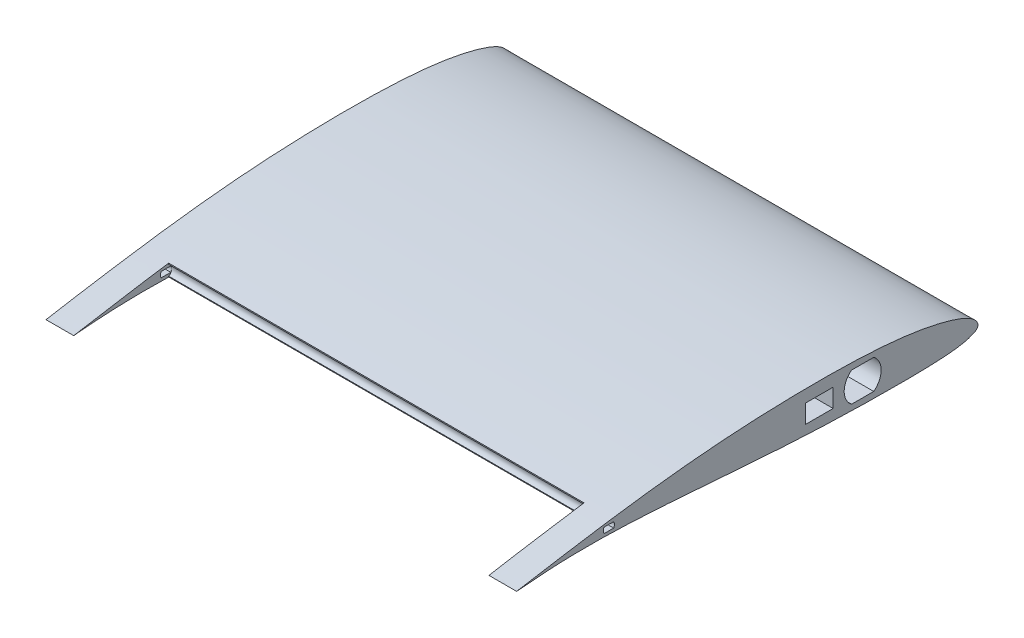
SolidWorks part; units mm, degrees
material "Foam"
ref_plane "Piano frontale" through (0, 0, 0) normal (0, 0, 1) x (1, 0, 0)
ref_plane "Piano superiore" through (0, 0, 0) normal (0, 1, 0) x (1, 0, 0)
ref_plane "Piano destro" through (0, 0, 0) normal (1, 0, 0) x (0, 0, -1)
curve "Curva1"
  spline degree 3 poles (0, 0.1724, 248.285) (0, -0.053, 250.4273) (0, 0.2462, 248.3284) (0, 0.5529, 246.6445) (0, 1.2459, 242.6221) (0, 2.0989, 237.7464) (0, 3.1818, 231.3634) (0, 4.2933, 223.9772) (0, 5.7312, 215.5604) (0, 7.1315, 206.3004) (0, 8.6324, 196.1631) (0, 10.1162, 185.3524) (0, 11.5493, 173.9891) (0, 12.8816, 162.1914) (0, 14.0593, 150.0724) (0, 15.0523, 137.7438) (0, 15.8256, 125.3116) (0, 16.3834, 112.8888) (0, 16.7267, 100.597) (0, 16.8648, 88.5669) (0, 16.792, 76.9314) (0, 16.4941, 65.8165) (0, 15.9609, 55.3329) (0, 15.1594, 45.573) (0, 14.0978, 36.6074) (0, 12.7884, 28.4972) (0, 11.2839, 21.2988) (0, 9.6413, 15.0749) (0, 7.9136, 9.8809) (0, 6.1182, 5.7699) (0, 4.2384, 2.7289) (0, 2.3057, 0.8126) (0, 0.7927, 0.0312) (0, -0.4105, -0.0213) (0, -1.7115, 0.4949) (0, -2.8658, 2.6253) (0, -4.0404, 5.6977) (0, -4.9287, 10.0719) (0, -5.5974, 15.6262) (0, -6.0122, 22.4122) (0, -6.265, 30.3619) (0, -6.3814, 39.3972) (0, -6.3554, 49.3987) (0, -6.2185, 60.2453) (0, -5.9476, 71.8018) (0, -5.5368, 83.9408) (0, -4.9386, 96.5461) (0, -4.1527, 109.5201) (0, -3.2196, 122.7671) (0, -2.1909, 136.1764) (0, -1.148, 149.6158) (0, -0.1602, 162.9314) (0, 0.706, 175.9537) (0, 1.3896, 188.4999) (0, 1.8332, 200.3712) (0, 1.9676, 211.3376) (0, 1.8232, 221.1842) (0, 1.4973, 229.6804) (0, 1.0741, 236.8065) (0, 0.6857, 242.1894) (0, 0.3087, 246.5181) (0, 0.1724, 248.285) (0, -0.053, 250.4273) (0, 0.2462, 248.3284) knots -0.014202 -0.006329 -0.001589 0 0.001576 0.006211 0.01368 0.023764 0.036307 0.051658 0.068045 0.086769 0.107053 0.128647 0.151303 0.174786 0.19886 0.223309 0.247929 0.272522 0.296848 0.320648 0.343669 0.365658 0.3864 0.405741 0.423561 0.439779 0.454311 0.467034 0.477831 0.486643 0.493542 0.498786 0.50271 0.50309 0.505896 0.510322 0.516831 0.525521 0.536535 0.549945 0.565696 0.583577 0.603379 0.624844 0.647727 0.671743 0.696673 0.722357 0.748609 0.77521 0.801891 0.828329 0.854175 0.879074 0.902636 0.924421 0.943939 0.960827 0.974827 0.985798 0.993671 0.998411 1 1.001576 1.006211 1.01368 periodic
sketch "Schizzo1" plane through (0, 0, 0) normal (1, 0, 0) x (0, 0, -1)
  line L0 (-250, 0) -> (0.0001, 0.0174) construction
  line L1 (0.0001, 0.0174) -> (-0.0034, 50.0174) construction
  line L2 (-62.4999, 16.3096) -> (-62.4999, -6.155) construction
  line L3 (-200, 8.0593) -> (-200, 1.7757) construction
  line L4 (-93.4999, 10.0773) -> (-78.4999, 10.0773)
  line L5 (-93.4999, 10.0773) -> (-93.4999, 0.0773)
  line L6 (-93.4999, 0.0773) -> (-78.4999, 0.0773)
  line L7 (-78.4999, 10.0773) -> (-78.4999, 0.0773)
  circle A0 centre (-62.4999, 5.0773) radius 8
  arc A1 (-200, 8.0593) -> (-200, 1.7757) centre (-200, 4.9175) cw
  spline S0 degree 3 poles (-248.3284, 0.2462) (-250.4273, -0.053) (-248.285, 0.1724) (-246.5181, 0.3087) (-242.1894, 0.6857) (-236.8065, 1.0741) (-229.6804, 1.4973) (-221.1842, 1.8232) (-211.3376, 1.9676) (-200.3712, 1.8332) (-188.4999, 1.3896) (-175.9537, 0.706) (-162.9314, -0.1602) (-149.6158, -1.148) (-136.1764, -2.1909) (-122.7671, -3.2196) (-109.5201, -4.1527) (-96.5461, -4.9386) (-83.9408, -5.5368) (-71.8018, -5.9476) (-60.2453, -6.2185) (-49.3987, -6.3554) (-39.3972, -6.3814) (-30.3619, -6.265) (-22.4122, -6.0122) (-15.6262, -5.5974) (-10.0719, -4.9287) (-5.6977, -4.0404) (-2.6253, -2.8658) (-0.4949, -1.7115) (0.0213, -0.4105) (-0.0312, 0.7927) (-0.8126, 2.3057) (-2.7289, 4.2384) (-5.7699, 6.1182) (-9.8809, 7.9136) (-15.0749, 9.6413) (-21.2988, 11.2839) (-28.4972, 12.7884) (-36.6074, 14.0978) (-45.573, 15.1594) (-55.3329, 15.9609) (-65.8165, 16.4941) (-76.9314, 16.792) (-88.5669, 16.8648) (-100.597, 16.7267) (-112.8888, 16.3834) (-125.3116, 15.8256) (-137.7438, 15.0523) (-150.0724, 14.0593) (-162.1914, 12.8816) (-173.9891, 11.5493) (-185.3524, 10.1162) (-196.1631, 8.6324) (-206.3004, 7.1315) (-215.5604, 5.7312) (-223.9772, 4.2933) (-231.3634, 3.1818) (-237.7464, 2.0989) (-242.6221, 1.2459) (-246.6445, 0.5529) (-248.3284, 0.2462) (-250.4273, -0.053) (-248.285, 0.1724) knots -0.01368 -0.006211 -0.001576 0 0.001589 0.006329 0.014202 0.025173 0.039173 0.056061 0.075579 0.097364 0.120926 0.145825 0.171671 0.198109 0.22479 0.251391 0.277643 0.303327 0.328257 0.352273 0.375156 0.396621 0.416423 0.434304 0.450055 0.463465 0.474479 0.483169 0.489678 0.494104 0.49691 0.49729 0.501214 0.506458 0.513357 0.522169 0.532966 0.545689 0.560221 0.576439 0.594259 0.6136 0.634342 0.656331 0.679352 0.703152 0.727478 0.752071 0.776691 0.80114 0.825214 0.848697 0.871353 0.892947 0.913231 0.931955 0.948342 0.963693 0.976236 0.98632 0.993789 0.998424 1 1.001589 1.006329 1.014202 only from (-250, 0) to (-250, 0) construction
  spline S1 degree 3 poles (-200, 1.7757) (-196.2415, 1.6788) (-188.276, 1.3774) (-175.9537, 0.706) (-162.9314, -0.1602) (-149.6158, -1.148) (-136.1764, -2.1909) (-122.7671, -3.2196) (-109.5201, -4.1527) (-96.5461, -4.9386) (-83.9408, -5.5368) (-71.8018, -5.9476) (-60.2453, -6.2185) (-49.3987, -6.3554) (-39.3972, -6.3814) (-30.3619, -6.265) (-22.4122, -6.0122) (-15.6262, -5.5974) (-10.0719, -4.9287) (-5.6977, -4.0404) (-2.6253, -2.8658) (-0.4949, -1.7115) (0.0213, -0.4105) (-0.0312, 0.7927) (-0.8126, 2.3057) (-2.7289, 4.2384) (-5.7699, 6.1182) (-9.8809, 7.9136) (-15.0749, 9.6413) (-21.2988, 11.2839) (-28.4972, 12.7884) (-36.6074, 14.0978) (-45.573, 15.1594) (-55.3329, 15.9609) (-65.8165, 16.4941) (-76.9314, 16.792) (-88.5669, 16.8648) (-100.597, 16.7267) (-112.8888, 16.3834) (-125.3116, 15.8256) (-137.7438, 15.0523) (-150.0724, 14.0593) (-162.1914, 12.8816) (-173.9891, 11.5493) (-185.3524, 10.1162) (-193.973, 8.933) (-198.7936, 8.2355) (-200, 8.0593) knots 0.09869 0.09869 0.09869 0.09869 0.120926 0.145825 0.171671 0.198109 0.22479 0.251391 0.277643 0.303327 0.328257 0.352273 0.375156 0.396621 0.416423 0.434304 0.450055 0.463465 0.474479 0.483169 0.489678 0.494104 0.49691 0.49729 0.501214 0.506458 0.513357 0.522169 0.532966 0.545689 0.560221 0.576439 0.594259 0.6136 0.634342 0.656331 0.679352 0.703152 0.727478 0.752071 0.776691 0.80114 0.825214 0.848697 0.871353 0.892947 0.900158 0.900158 0.900158 0.900158
  point P12 (-78.4999, 5.0773)
  dimension "D3" = 16
  dimension "D1" = 50
  dimension "D2" = 62.5
  dimension "D4" = 15
  dimension "D5" = 10
  dimension "D6" = 16
  dimension "D7" = 50
  dimension "D8" = 6.2836
extrude "CorpoFoam" add sketch "Schizzo1" along normal blind 225
sketch "Schizzo2" plane through (225, 0, 0) normal (1, 0, 0) x (0, 0, -1)
  line L0 (-200, 8.0593) -> (-200, 1.7757) construction
  line L1 (-203.5, 8.2775) -> (-198.5, 8.2775)
  line L2 (-203.5, 8.2775) -> (-203.5, 1.7346)
  line L3 (-203.5, 1.7346) -> (-198.5, 1.7346)
  line L4 (-198.5, 8.2775) -> (-198.5, 1.7346)
  arc A0 (-200, 1.7757) -> (-200, 8.0593) centre (-200, 4.9175) ccw construction
  spline S0 degree 3 poles (-248.3284, 0.2462) (-250.4273, -0.053) (-248.285, 0.1724) (-246.5181, 0.3087) (-242.1894, 0.6857) (-236.8065, 1.0741) (-229.6804, 1.4973) (-221.1842, 1.8232) (-211.3376, 1.9676) (-200.3712, 1.8332) (-188.4999, 1.3896) (-175.9537, 0.706) (-162.9314, -0.1602) (-149.6158, -1.148) (-136.1764, -2.1909) (-122.7671, -3.2196) (-109.5201, -4.1527) (-96.5461, -4.9386) (-83.9408, -5.5368) (-71.8018, -5.9476) (-60.2453, -6.2185) (-49.3987, -6.3554) (-39.3972, -6.3814) (-30.3619, -6.265) (-22.4122, -6.0122) (-15.6262, -5.5974) (-10.0719, -4.9287) (-5.6977, -4.0404) (-2.6253, -2.8658) (-0.4949, -1.7115) (0.0213, -0.4105) (-0.0312, 0.7927) (-0.8126, 2.3057) (-2.7289, 4.2384) (-5.7699, 6.1182) (-9.8809, 7.9136) (-15.0749, 9.6413) (-21.2988, 11.2839) (-28.4972, 12.7884) (-36.6074, 14.0978) (-45.573, 15.1594) (-55.3329, 15.9609) (-65.8165, 16.4941) (-76.9314, 16.792) (-88.5669, 16.8648) (-100.597, 16.7267) (-112.8888, 16.3834) (-125.3116, 15.8256) (-137.7438, 15.0523) (-150.0724, 14.0593) (-162.1914, 12.8816) (-173.9891, 11.5493) (-185.3524, 10.1162) (-196.1631, 8.6324) (-206.3004, 7.1315) (-215.5604, 5.7312) (-223.9772, 4.2933) (-231.3634, 3.1818) (-237.7464, 2.0989) (-242.6221, 1.2459) (-246.6445, 0.5529) (-248.3284, 0.2462) (-250.4273, -0.053) (-248.285, 0.1724) knots -0.01368 -0.006211 -0.001576 0 0.001589 0.006329 0.014202 0.025173 0.039173 0.056061 0.075579 0.097364 0.120926 0.145825 0.171671 0.198109 0.22479 0.251391 0.277643 0.303327 0.328257 0.352273 0.375156 0.396621 0.416423 0.434304 0.450055 0.463465 0.474479 0.483169 0.489678 0.494104 0.49691 0.49729 0.501214 0.506458 0.513357 0.522169 0.532966 0.545689 0.560221 0.576439 0.594259 0.6136 0.634342 0.656331 0.679352 0.703152 0.727478 0.752071 0.776691 0.80114 0.825214 0.848697 0.871353 0.892947 0.913231 0.931955 0.948342 0.963693 0.976236 0.98632 0.993789 0.998424 1 1.001589 1.006329 1.014202 only from (-250, 0) to (-250, 0) construction
  dimension "D1" = 5
  dimension "D2" = 1.5
extrude "SmussoPosteriore" cut sketch "Schizzo2" against normal through all
sketch "Schizzo3" plane through (225, 0, 0) normal (1, 0, 0) x (0, 0, -1)
  line L1 (-93.4999, 10.0773) -> (-78.4999, 10.0773)
  line L2 (-93.4999, 10.0773) -> (-93.4999, 0.0773)
  line L3 (-93.4999, 0.0773) -> (-78.4999, 0.0773)
  line L4 (-78.4999, 10.0773) -> (-78.4999, 0.0773)
  circle A0 centre (-62.4999, 5.0773) radius 8
  circle A1 centre (-62.4999, 5.0773) radius 8 construction
  spline S0 degree 3 poles (-248.3284, 0.2462) (-250.4273, -0.053) (-248.285, 0.1724) (-246.5181, 0.3087) (-242.1894, 0.6857) (-236.8065, 1.0741) (-229.6804, 1.4973) (-221.1842, 1.8232) (-211.3376, 1.9676) (-200.3712, 1.8332) (-188.4999, 1.3896) (-175.9537, 0.706) (-162.9314, -0.1602) (-149.6158, -1.148) (-136.1764, -2.1909) (-122.7671, -3.2196) (-109.5201, -4.1527) (-96.5461, -4.9386) (-83.9408, -5.5368) (-71.8018, -5.9476) (-60.2453, -6.2185) (-49.3987, -6.3554) (-39.3972, -6.3814) (-30.3619, -6.265) (-22.4122, -6.0122) (-15.6262, -5.5974) (-10.0719, -4.9287) (-5.6977, -4.0404) (-2.6253, -2.8658) (-0.4949, -1.7115) (0.0213, -0.4105) (-0.0312, 0.7927) (-0.8126, 2.3057) (-2.7289, 4.2384) (-5.7699, 6.1182) (-9.8809, 7.9136) (-15.0749, 9.6413) (-21.2988, 11.2839) (-28.4972, 12.7884) (-36.6074, 14.0978) (-45.573, 15.1594) (-55.3329, 15.9609) (-65.8165, 16.4941) (-76.9314, 16.792) (-88.5669, 16.8648) (-100.597, 16.7267) (-112.8888, 16.3834) (-125.3116, 15.8256) (-137.7438, 15.0523) (-150.0724, 14.0593) (-162.1914, 12.8816) (-173.9891, 11.5493) (-185.3524, 10.1162) (-196.1631, 8.6324) (-206.3004, 7.1315) (-215.5604, 5.7312) (-223.9772, 4.2933) (-231.3634, 3.1818) (-237.7464, 2.0989) (-242.6221, 1.2459) (-246.6445, 0.5529) (-248.3284, 0.2462) (-250.4273, -0.053) (-248.285, 0.1724) knots -0.01368 -0.006211 -0.001576 0 0.001589 0.006329 0.014202 0.025173 0.039173 0.056061 0.075579 0.097364 0.120926 0.145825 0.171671 0.198109 0.22479 0.251391 0.277643 0.303327 0.328257 0.352273 0.375156 0.396621 0.416423 0.434304 0.450055 0.463465 0.474479 0.483169 0.489678 0.494104 0.49691 0.49729 0.501214 0.506458 0.513357 0.522169 0.532966 0.545689 0.560221 0.576439 0.594259 0.6136 0.634342 0.656331 0.679352 0.703152 0.727478 0.752071 0.776691 0.80114 0.825214 0.848697 0.871353 0.892947 0.913231 0.931955 0.948342 0.963693 0.976236 0.98632 0.993789 0.998424 1 1.001589 1.006329 1.014202 only from (-250, 0) to (-250, 0) construction
  spline S1 degree 3 poles (-248.3284, 0.2462) (-250.4273, -0.053) (-248.285, 0.1724) (-246.5181, 0.3087) (-242.1894, 0.6857) (-236.8065, 1.0741) (-229.6804, 1.4973) (-221.1842, 1.8232) (-211.3376, 1.9676) (-200.3712, 1.8332) (-188.4999, 1.3896) (-175.9537, 0.706) (-162.9314, -0.1602) (-149.6158, -1.148) (-136.1764, -2.1909) (-122.7671, -3.2196) (-109.5201, -4.1527) (-96.5461, -4.9386) (-83.9408, -5.5368) (-71.8018, -5.9476) (-60.2453, -6.2185) (-49.3987, -6.3554) (-39.3972, -6.3814) (-30.3619, -6.265) (-22.4122, -6.0122) (-15.6262, -5.5974) (-10.0719, -4.9287) (-5.6977, -4.0404) (-2.6253, -2.8658) (-0.4949, -1.7115) (0.0213, -0.4105) (-0.0312, 0.7927) (-0.8126, 2.3057) (-2.7289, 4.2384) (-5.7699, 6.1182) (-9.8809, 7.9136) (-15.0749, 9.6413) (-21.2988, 11.2839) (-28.4972, 12.7884) (-36.6074, 14.0978) (-45.573, 15.1594) (-55.3329, 15.9609) (-65.8165, 16.4941) (-76.9314, 16.792) (-88.5669, 16.8648) (-100.597, 16.7267) (-112.8888, 16.3834) (-125.3116, 15.8256) (-137.7438, 15.0523) (-150.0724, 14.0593) (-162.1914, 12.8816) (-173.9891, 11.5493) (-185.3524, 10.1162) (-196.1631, 8.6324) (-206.3004, 7.1315) (-215.5604, 5.7312) (-223.9772, 4.2933) (-231.3634, 3.1818) (-237.7464, 2.0989) (-242.6221, 1.2459) (-246.6445, 0.5529) (-248.3284, 0.2462) (-250.4273, -0.053) (-248.285, 0.1724) knots -0.01368 -0.006211 -0.001576 0 0.001589 0.006329 0.014202 0.025173 0.039173 0.056061 0.075579 0.097364 0.120926 0.145825 0.171671 0.198109 0.22479 0.251391 0.277643 0.303327 0.328257 0.352273 0.375156 0.396621 0.416423 0.434304 0.450055 0.463465 0.474479 0.483169 0.489678 0.494104 0.49691 0.49729 0.501214 0.506458 0.513357 0.522169 0.532966 0.545689 0.560221 0.576439 0.594259 0.6136 0.634342 0.656331 0.679352 0.703152 0.727478 0.752071 0.776691 0.80114 0.825214 0.848697 0.871353 0.892947 0.913231 0.931955 0.948342 0.963693 0.976236 0.98632 0.993789 0.998424 1 1.001589 1.006329 1.014202 only from (-250, 0) to (-250, 0)
extrude "LatoDestro" add sketch "Schizzo3" along normal blind 15
sketch "Schizzo4" plane through (0, 0, 0) normal (-1, 0, 0) x (0, 0, 1)
  line L1 (78.4999, 10.0773) -> (93.4999, 10.0773)
  line L2 (78.4999, 10.0773) -> (78.4999, 0.0773)
  line L3 (78.4999, 0.0773) -> (93.4999, 0.0773)
  line L4 (93.4999, 10.0773) -> (93.4999, 0.0773)
  circle A0 centre (62.4999, 5.0773) radius 8
  circle A1 centre (62.4999, 5.0773) radius 8 construction
  spline S0 degree 3 poles (248.285, 0.1724) (250.4273, -0.053) (248.3284, 0.2462) (246.6445, 0.5529) (242.6221, 1.2459) (237.7464, 2.0989) (231.3634, 3.1818) (223.9772, 4.2933) (215.5604, 5.7312) (206.3004, 7.1315) (196.1631, 8.6324) (185.3524, 10.1162) (173.9891, 11.5493) (162.1914, 12.8816) (150.0724, 14.0593) (137.7438, 15.0523) (125.3116, 15.8256) (112.8888, 16.3834) (100.597, 16.7267) (88.5669, 16.8648) (76.9314, 16.792) (65.8165, 16.4941) (55.3329, 15.9609) (45.573, 15.1594) (36.6074, 14.0978) (28.4972, 12.7884) (21.2988, 11.2839) (15.0749, 9.6413) (9.8809, 7.9136) (5.7699, 6.1182) (2.7289, 4.2384) (0.8126, 2.3057) (0.0312, 0.7927) (-0.0213, -0.4105) (0.4949, -1.7115) (2.6253, -2.8658) (5.6977, -4.0404) (10.0719, -4.9287) (15.6262, -5.5974) (22.4122, -6.0122) (30.3619, -6.265) (39.3972, -6.3814) (49.3987, -6.3554) (60.2453, -6.2185) (71.8018, -5.9476) (83.9408, -5.5368) (96.5461, -4.9386) (109.5201, -4.1527) (122.7671, -3.2196) (136.1764, -2.1909) (149.6158, -1.148) (162.9314, -0.1602) (175.9537, 0.706) (188.4999, 1.3896) (200.3712, 1.8332) (211.3376, 1.9676) (221.1842, 1.8232) (229.6804, 1.4973) (236.8065, 1.0741) (242.1894, 0.6857) (246.5181, 0.3087) (248.285, 0.1724) (250.4273, -0.053) (248.3284, 0.2462) knots -0.014202 -0.006329 -0.001589 0 0.001576 0.006211 0.01368 0.023764 0.036307 0.051658 0.068045 0.086769 0.107053 0.128647 0.151303 0.174786 0.19886 0.223309 0.247929 0.272522 0.296848 0.320648 0.343669 0.365658 0.3864 0.405741 0.423561 0.439779 0.454311 0.467034 0.477831 0.486643 0.493542 0.498786 0.50271 0.50309 0.505896 0.510322 0.516831 0.525521 0.536535 0.549945 0.565696 0.583577 0.603379 0.624844 0.647727 0.671743 0.696673 0.722357 0.748609 0.77521 0.801891 0.828329 0.854175 0.879074 0.902636 0.924421 0.943939 0.960827 0.974827 0.985798 0.993671 0.998411 1 1.001576 1.006211 1.01368 only from (250, 0) to (250, 0) construction
  spline S1 degree 3 poles (248.285, 0.1724) (250.4273, -0.053) (248.3284, 0.2462) (246.6445, 0.5529) (242.6221, 1.2459) (237.7464, 2.0989) (231.3634, 3.1818) (223.9772, 4.2933) (215.5604, 5.7312) (206.3004, 7.1315) (196.1631, 8.6324) (185.3524, 10.1162) (173.9891, 11.5493) (162.1914, 12.8816) (150.0724, 14.0593) (137.7438, 15.0523) (125.3116, 15.8256) (112.8888, 16.3834) (100.597, 16.7267) (88.5669, 16.8648) (76.9314, 16.792) (65.8165, 16.4941) (55.3329, 15.9609) (45.573, 15.1594) (36.6074, 14.0978) (28.4972, 12.7884) (21.2988, 11.2839) (15.0749, 9.6413) (9.8809, 7.9136) (5.7699, 6.1182) (2.7289, 4.2384) (0.8126, 2.3057) (0.0312, 0.7927) (-0.0213, -0.4105) (0.4949, -1.7115) (2.6253, -2.8658) (5.6977, -4.0404) (10.0719, -4.9287) (15.6262, -5.5974) (22.4122, -6.0122) (30.3619, -6.265) (39.3972, -6.3814) (49.3987, -6.3554) (60.2453, -6.2185) (71.8018, -5.9476) (83.9408, -5.5368) (96.5461, -4.9386) (109.5201, -4.1527) (122.7671, -3.2196) (136.1764, -2.1909) (149.6158, -1.148) (162.9314, -0.1602) (175.9537, 0.706) (188.4999, 1.3896) (200.3712, 1.8332) (211.3376, 1.9676) (221.1842, 1.8232) (229.6804, 1.4973) (236.8065, 1.0741) (242.1894, 0.6857) (246.5181, 0.3087) (248.285, 0.1724) (250.4273, -0.053) (248.3284, 0.2462) knots -0.014202 -0.006329 -0.001589 0 0.001576 0.006211 0.01368 0.023764 0.036307 0.051658 0.068045 0.086769 0.107053 0.128647 0.151303 0.174786 0.19886 0.223309 0.247929 0.272522 0.296848 0.320648 0.343669 0.365658 0.3864 0.405741 0.423561 0.439779 0.454311 0.467034 0.477831 0.486643 0.493542 0.498786 0.50271 0.50309 0.505896 0.510322 0.516831 0.525521 0.536535 0.549945 0.565696 0.583577 0.603379 0.624844 0.647727 0.671743 0.696673 0.722357 0.748609 0.77521 0.801891 0.828329 0.854175 0.879074 0.902636 0.924421 0.943939 0.960827 0.974827 0.985798 0.993671 0.998411 1 1.001576 1.006211 1.01368 only from (250, 0) to (250, 0)
extrude "LatoSinistro" add sketch "Schizzo4" along normal blind 15
sketch "Schizzo5" plane through (-15, 0, 0) normal (-1, 0, 0) x (0, 0, 1)
  line L1 (197.4019, 6.4175) -> (202.5981, 6.4175)
  line L3 (197.4019, 3.4175) -> (202.5981, 3.4175)
  circle A0 centre (200, 4.9175) radius 1.5 construction
  arc A1 (197.4019, 6.4175) -> (197.4019, 3.4175) centre (200, 4.9175) ccw
  arc A2 (202.5981, 3.4175) -> (202.5981, 6.4175) centre (200, 4.9175) ccw
  dimension "D1" = 3
  dimension "D2" = 6
extrude "ForoPernoAlettone" cut sketch "Schizzo5" against normal through all
sketch "Schizzo6" plane through (240, 0, 0) normal (1, 0, 0) x (0, 0, -1)
  line L1 (-68.4999, 13.0773) -> (-56.4999, 13.0773)
  line L3 (-68.4999, -2.9227) -> (-56.4999, -2.9227)
  arc A0 (-68.4999, 13.0773) -> (-68.4999, -2.9227) centre (-62.4999, 5.0773) ccw
  circle A1 centre (-62.4999, 5.0773) radius 8 construction
  arc A2 (-56.4999, -2.9227) -> (-56.4999, 13.0773) centre (-62.4999, 5.0773) ccw
  dimension "D1" = 20
extrude "ForoFoamLongherone" cut sketch "Schizzo6" against normal blind 15
